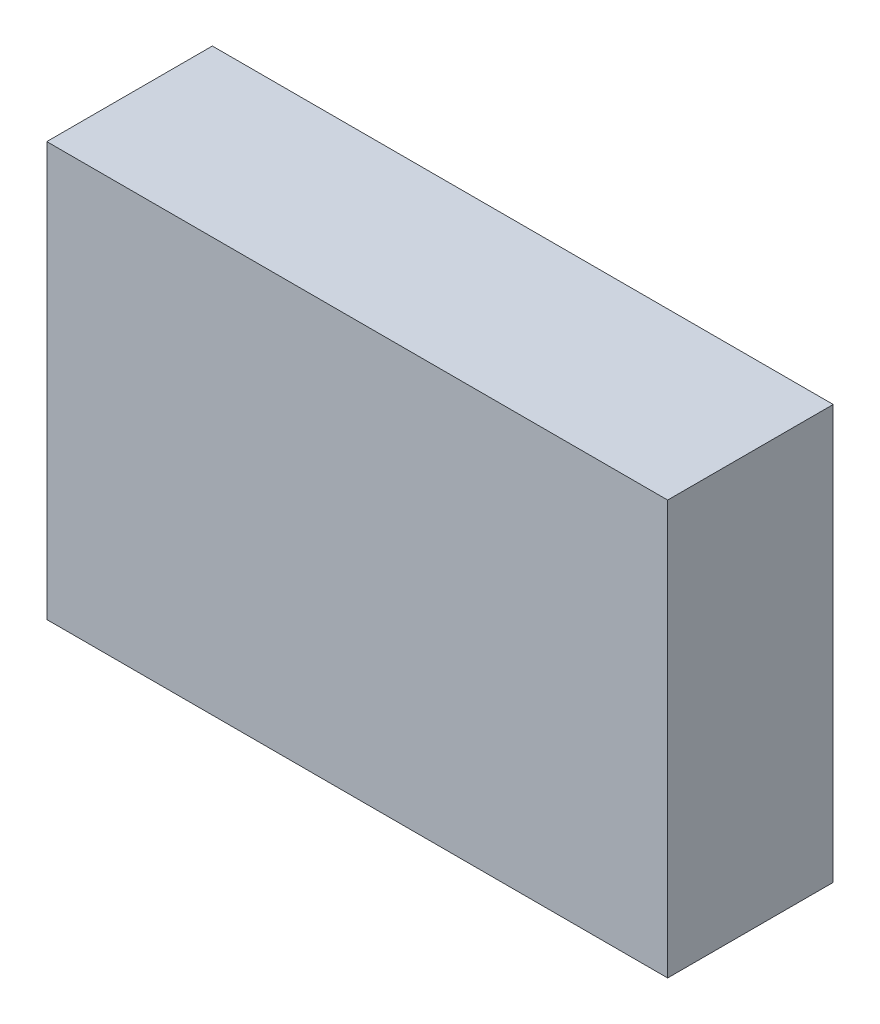
SolidWorks part; units mm, degrees
ref_plane "Front Plane" through (0, 0, 0) normal (0, 0, 1) x (1, 0, 0)
ref_plane "Top Plane" through (0, 0, 0) normal (0, 1, 0) x (1, 0, 0)
ref_plane "Right Plane" through (0, 0, 0) normal (1, 0, 0) x (0, 0, -1)
sketch "Sketch1" plane through (0, 0, 0) normal (0, 0, 1) x (1, 0, 0)
  line L1 (-18.75, -12.5) -> (18.75, -12.5)
  line L2 (-18.75, -12.5) -> (-18.75, 12.5)
  line L3 (-18.75, 12.5) -> (18.75, 12.5)
  line L4 (18.75, -12.5) -> (18.75, 12.5)
  line L5 (-18.75, -12.5) -> (18.75, 12.5) construction
  line L6 (-18.75, 12.5) -> (18.75, -12.5) construction
  point P0 (0, 0)
  dimension "D1" = 25
  dimension "D2" = 37.5
extrude "Boss-Extrude1" add sketch "Sketch1" along normal blind 10
